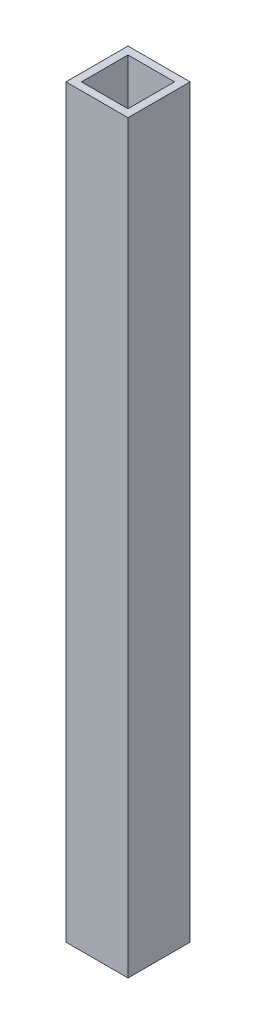
SolidWorks part; units mm, degrees
ref_plane "Front Plane" through (0, 0, 0) normal (0, 0, 1) x (1, 0, 0)
ref_plane "Top Plane" through (0, 0, 0) normal (0, 1, 0) x (1, 0, 0)
ref_plane "Right Plane" through (0, 0, 0) normal (1, 0, 0) x (0, 0, -1)
sketch "Sketch1" plane through (0, 0, 0) normal (0, 1, 0) x (1, 0, 0)
  line L1 (-12.7, 12.7) -> (12.7, 12.7)
  line L2 (-12.7, 12.7) -> (-12.7, -12.7)
  line L3 (-12.7, -12.7) -> (12.7, -12.7)
  line L4 (12.7, 12.7) -> (12.7, -12.7)
  line L5 (-12.7, 12.7) -> (12.7, -12.7) construction
  line L6 (-12.7, -12.7) -> (12.7, 12.7) construction
  point P0 (0, 0)
  dimension "D1" = 25.4
  dimension "D2" = 25.4
extrude "Boss-Extrude1" add sketch "Sketch1" along normal blind 304.8
shell "Shell1" thickness 3.175
